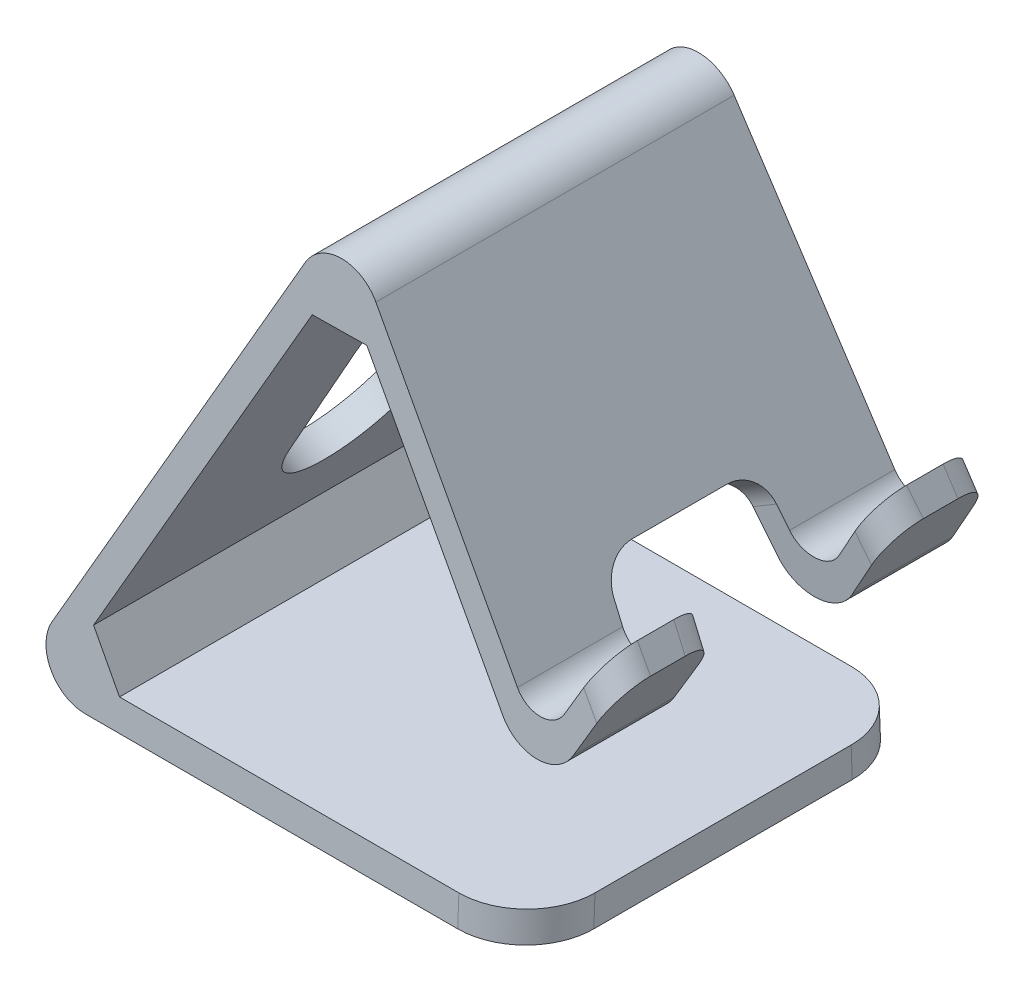
SolidWorks part; units mm, degrees
material "6061 合金"
ref_plane "前视基准面" through (0, 0, 0) normal (0, 0, 1) x (1, 0, 0)
ref_plane "上视基准面" through (0, 0, 0) normal (0, 1, 0) x (1, 0, 0)
ref_plane "右视基准面" through (0, 0, 0) normal (1, 0, 0) x (0, 0, -1)
other "Configuration Table"
sketch "草图32" plane through (0, 0, 0) normal (0, 0, 1) x (1, 0, 0)
  line L0 (0, 0) -> (-67.8794, 0)
  line L1 (-67.8794, 0) -> (-29.8995, 67.5198)
  line L2 (-29.8995, 67.5198) -> (0.762, 16.0877)
  line L3 (0.762, 16.0877) -> (11.9312, 35.4334)
  line L4 (11.9312, 35.4334) -> (9.8781, 38.8773)
  line L5 (9.8781, 38.8773) -> (1, 23.5)
  line L6 (1, 23.5) -> (-30, 75.5)
  line L7 (-30, 75.5) -> (-75, -4.5)
  line L8 (-75, -4.5) -> (0, -4.5)
  line L9 (0, -4.5) -> (0, 0)
  point P10 (0, 0)
  point P12 (0, 0)
  point P13 (-27.7533, 72.2551)
  dimension "D1" = 75
  dimension "D2" = 45
  dimension "D3" = 80
  dimension "D4" = 31
  dimension "D5" = 15.5
  dimension "D6" = 4
  dimension "D7" = 60
  dimension "D8" = 4
  dimension "D9" = 4.5
  dimension "D10" = 3.5
  dimension "D11" = 28
extrude "凸台-拉伸3" add sketch "草图32" along normal mid plane 58
sketch "草图33" plane through (0, 0, 0) normal (1, 0, 0) x (0, 0, -1)
  line L0 (-29, -4.5) -> (-26, 75.5)
  line L1 (-29, 75.5) -> (29, 75.5) construction
  line L2 (-26, 75.5) -> (-29, 75.5)
  line L3 (-29, 75.5) -> (-29, -4.5)
  line L4 (0, -4.5) -> (0, 75.5) construction
  line L5 (-29, -4.5) -> (29, -4.5) construction
  line L6 (29, 75.5) -> (29, -4.5)
  line L7 (26, 75.5) -> (29, 75.5)
  line L8 (29, -4.5) -> (26, 75.5)
  dimension "D1" = 52
extrude "切除-拉伸3" cut sketch "草图33" against normal through all both and the other way through all
sketch "草图34" plane through (11.0739, 6.6018, 0) normal (0.8589, 0.5121, 0) x (0, 0, -1)
  line L0 (0, 0) -> (0, 34.1347) construction
  line L1 (11.5, 34.1347) -> (-11.5, 34.1347)
  line L2 (-11.5, 34.1347) -> (-14, 9.1347)
  line L3 (-14, 9.1347) -> (14, 9.1347)
  line L4 (11.5, 34.1347) -> (14, 9.1347)
  line L5 (-29, -3.8653) -> (29, -3.8653) construction
  point P7 (0, 9.1347)
  point P8 (0, 0)
  dimension "D1" = 23
  dimension "D2" = 28
  dimension "D3" = 13
  dimension "D4" = 25
extrude "切除-拉伸4" cut sketch "草图34" against normal up to next and the other way through all
fillet "圆角3" radius 10 2 edges at (0, -2.25, -28.9156) (0, -2.25, 28.9156)
chamfer "倒角2" distance 8 2 edges at (-67.8794, 0, 0) (-29.8995, 67.5198, 0)
fillet "圆角4" radius 6 2 edges at (-75, -4.5, 0) (-30, 75.5, 0)
fillet "圆角5" radius 4 2 edges at (1, 23.5, 20.4481) (1, 23.5, -20.4481)
fillet "圆角6" radius 6 2 edges at (0.762, 16.0877, 20.8993) (0.762, 16.0877, -20.8993)
fillet "圆角7" radius 5 4 edges at (10.9047, 37.1554, 27.4379) (10.9047, 37.1554, 12.2804) (10.9047, 37.1554, -12.2804) (10.9047, 37.1554, -27.4379)
sketch "草图35" plane through (0, -4.5, 0) normal (0, -1, 0) x (1, 0, 0)
  line L0 (0, 0) -> (-64.7409, 0) construction
  line L1 (-64.7409, 29) -> (-64.7409, -29) construction
  circle A0 centre (-10, 18.993) radius 7.5
  circle A1 centre (-10, -18.993) radius 7.5
  circle A2 centre (-58, 0) radius 7.5
  ellipse E0 centre (-10, -18.993) end of major axis (-10, -29) minor radius 10 (-10, -29) -> (0, -18.993) ccw construction
  ellipse E1 centre (-10, 18.993) end of major axis (-10, 8.9859) minor radius 10 (0, 18.993) -> (-10, 29) ccw construction
  point P11 (-59.9854, 0)
  dimension "D1" = 15
  dimension "D2" = 58
extrude "凸台-拉伸5" add sketch "草图35" along normal blind 1
sketch "草图36" plane through (-55.0504, 30.9659, 0) normal (-0.8716, 0.4903, 0) x (0, 0, 1)
  line L0 (0, -36.4326) -> (0, 46.7371) construction
  line L1 (-28.9711, -36.4326) -> (28.9711, -36.4326) construction
  line L2 (26.2528, 46.7371) -> (-26.2528, 46.7371) construction
  line L3 (0, -4.4326) -> (0, 15.5674) construction
  line L4 (-10, -4.4326) -> (-10, 15.5674)
  line L5 (10, -4.4326) -> (10, 15.5674)
  arc A0 (-10, -4.4326) -> (10, -4.4326) centre (0, -4.4326) ccw
  arc A1 (10, 15.5674) -> (-10, 15.5674) centre (0, 15.5674) ccw
  point P8 (0, 5.5674)
  dimension "D1" = 20
  dimension "D2" = 20
  dimension "D3" = 32
extrude "切除-拉伸5" cut sketch "草图36" against normal up to next
sketch "草图37" plane through (-55.0504, 30.9659, 0) normal (-0.8716, 0.4903, 0) x (0, 0, 1)
  text T0 "SOLIDWOKS" font "华光胖头鱼_CNKI" height 5
extrude "切除-拉伸6" cut sketch "草图37" against normal blind 0.3
fillet "圆角8" radius 5 2 edges at (-8.1231, 34.8976, -11.5) (-8.1231, 34.8976, 11.5)
